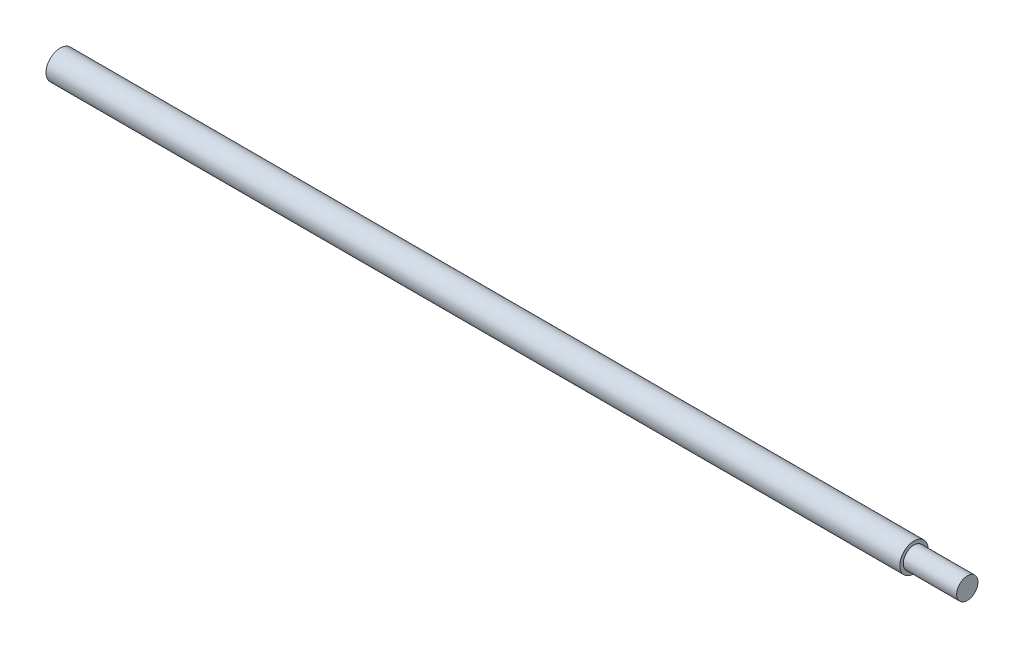
SolidWorks part; units mm, degrees
ref_plane "Front Plane" through (0, 0, 0) normal (0, 0, 1) x (1, 0, 0)
ref_plane "Top Plane" through (0, 0, 0) normal (0, 1, 0) x (1, 0, 0)
ref_plane "Right Plane" through (0, 0, 0) normal (1, 0, 0) x (0, 0, -1)
sketch "Sketch1" plane through (0, 0, 0) normal (0, 0, 1) x (1, 0, 0)
  line L0 (-127.5, 0) -> (-127.5, 4)
  line L1 (-127.5, 4) -> (112.5, 4)
  line L2 (112.5, 4) -> (112.5, 3)
  line L3 (112.5, 3) -> (127.5, 3)
  line L4 (127.5, 3) -> (127.5, 0)
  line L5 (127.5, 0) -> (-127.5, 0)
  line L6 (277.0819, 0) -> (-277.0819, 0) construction
  line L7 (0, -63.7054) -> (0, 63.7054) construction
  point P10 (0, 0)
  point P14 (0, 0)
  dimension "D1" = 255
  dimension "D2" = 15
  dimension "D3" = 8
  dimension "D4" = 6
revolve "Revolve1" add sketch "Sketch1" angle 360 about L6
cosmetic thread "Cosmetic Thread1" parameters "D2"=7
cosmetic thread "Cosmetic Thread2" parameters "D2"=5
